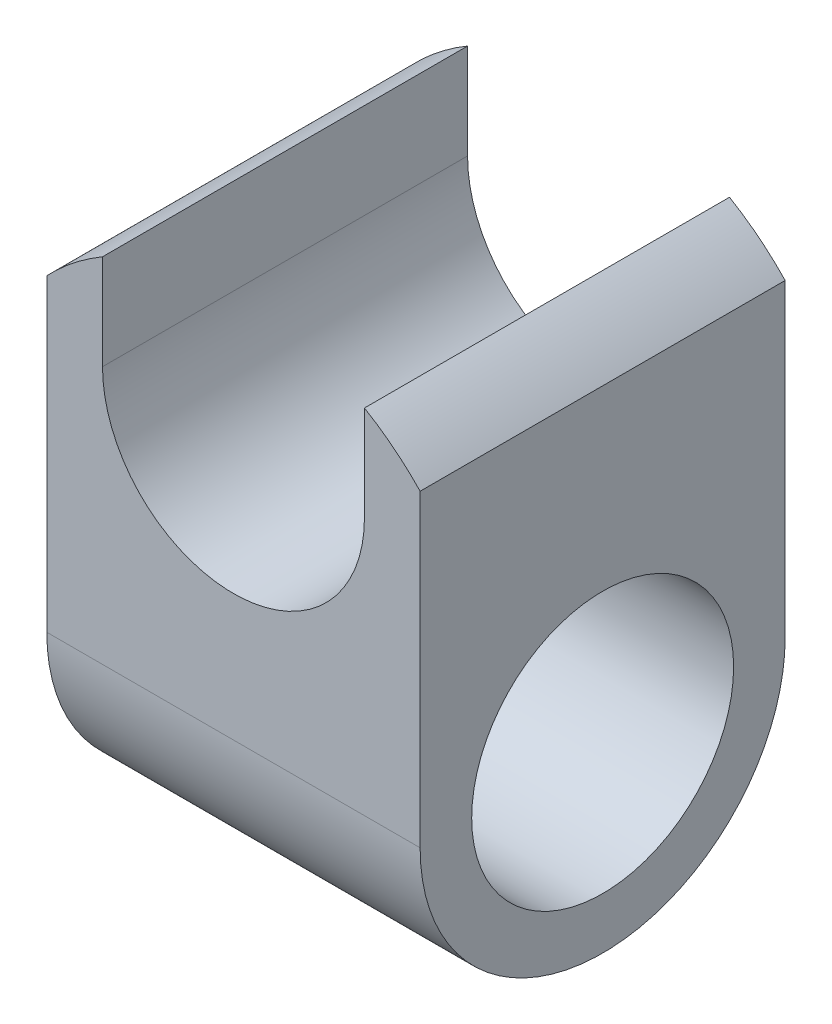
SolidWorks part; units mm, degrees
ref_plane "Front Plane" through (0, 0, 0) normal (0, 0, 1) x (1, 0, 0)
ref_plane "Top Plane" through (0, 0, 0) normal (0, 1, 0) x (1, 0, 0)
ref_plane "Right Plane" through (0, 0, 0) normal (1, 0, 0) x (0, 0, -1)
sketch "Sketch1" plane through (0, 0, 0) normal (0, 0, 1) x (1, 0, 0)
  line L3 (-6.35, 0) -> (-6.35, 5.9351)
  line L4 (6.35, 0) -> (6.35, 5.9351)
  line L5 (-9.05, 0) -> (-9.05, 5.4998)
  line L6 (9.05, 0) -> (9.05, 5.4998)
  arc A1 (-6.35, 0) -> (6.35, 0) centre (0, 0) ccw
  arc A2 (-9.05, 0) -> (9.05, 0) centre (0, 0) ccw
  circle A3 centre (0, 0) radius 9.05 construction
  circle A4 centre (0, 0) radius 6.35 construction
  ellipse E0 centre (0, -18.65) end of major axis (35, -18.65) minor radius 25 (-6.35, 5.9351) -> (-9.05, 5.4998) ccw
  ellipse E1 centre (0, -18.65) end of major axis (-35, -18.65) minor radius 25 (9.05, 5.4998) -> (6.35, 5.9351) ccw
  dimension "D1" = 12.7
  dimension "D2" = 2.7
  dimension "D3" = 25
  dimension "D4" = 35
extrude "Body spar link" add sketch "Sketch1" along normal mid plane 17.7
sketch "Sketch2" plane through (0, 0, 0) normal (1, 0, 0) x (0, 0, -1)
  line L1 (-8.85, -12.5) -> (-8.85, -2.5)
  line L6 (8.85, -2.5) -> (8.85, -12.5)
  line L8 (-8.85, -2.5) -> (8.85, -2.5)
  line L9 (-8.85, 0) -> (-8.85, -9.05) construction
  line L10 (8.85, -9.05) -> (8.85, 0) construction
  circle A0 centre (0, -12.5) radius 6.35
  arc A1 (-8.85, -12.5) -> (8.85, -12.5) centre (0, -12.5) ccw
  circle A2 centre (0, -12.5) radius 8.85 construction
  dimension "D1" = 12.7
  dimension "D3" = 2.5
  dimension "D4" = 10
  dimension "D2" = 2.5
extrude "Wing spar extrude" add sketch "Sketch2" along normal mid plane 18.1
sketch "Sketch3" plane through (0, -2.5, 0) normal (0, 1, 0) x (1, 0, 0)
  line L4 (9.05, 8.85) -> (8.6978, 8.85)
  line L5 (8.6978, 8.85) -> (8.6978, -8.85)
  line L6 (8.6978, -8.85) -> (9.05, -8.85)
  line L8 (9.05, 8.85) -> (8.6978, 8.85)
  line L10 (8.6978, -8.85) -> (9.05, -8.85)
  line L12 (-9.05, -8.85) -> (-8.6978, -8.85)
  line L13 (-8.6978, -8.85) -> (-8.6978, 8.85)
  line L14 (-8.6978, 8.85) -> (-9.05, 8.85)
  line L16 (-9.05, -8.85) -> (-8.6978, -8.85)
  line L18 (-8.6978, 8.85) -> (-9.05, 8.85)
  line L22 (-8.6978, -8.85) -> (-8.6978, 8.85)
  line L26 (8.6978, 8.85) -> (8.6978, -8.85)
  line L28 (-9.05, 8.85) -> (-9.05, -8.85)
  line L29 (-9.05, 8.85) -> (-9.05, -8.85)
  line L30 (9.05, -8.85) -> (9.05, 8.85)
  line L31 (9.05, -8.85) -> (9.05, 8.85)
  dimension "D1" = 0
  dimension "D2" = 0
extrude "Small cut completion" add sketch "Sketch3" along normal up to next
sketch "Sketch4" plane through (0, 0, -8.85) normal (0, 0, -1) x (-1, 0, 0)
  circle A0 centre (0, 0) radius 6.35
  arc A1 (5.8372, -2.5) -> (6.35, 0) centre (0, 0) ccw construction
extrude "Cut cleanup" cut sketch "Sketch4" against normal through all both and the other way through all
sketch "Sketch5" plane through (0, 0, -8.85) normal (0, 0, -1) x (-1, 0, 0)
  line L0 (-12.5, -6.15) -> (-22.5, -6.15)
  line L1 (12.5, -6.15) -> (22.5, -6.15)
  circle A0 centre (0, 0) radius 6.35 construction
  arc A1 (-6.35, 0) -> (6.35, 0) centre (0, 0) ccw construction
  arc A2 (12.5, -6.15) -> (-12.5, -6.15) centre (0, -6.15) ccw
  arc A3 (22.5, -6.15) -> (-22.5, -6.15) centre (0, -6.15) ccw
  circle A4 centre (0, -6.15) radius 12.5 construction
  circle A5 centre (0, -6.15) radius 22.5 construction
  dimension "D1" = 25
  dimension "D2" = 10
extrude "Edge rounding (to fit end cap of fuselage)" cut sketch "Sketch5" against normal through all both and the other way through all
sketch "Sketch6" plane through (9.05, 0, 0) normal (1, 0, 0) x (0, 0, -1)
  circle A0 centre (0, -12.5) radius 6.35 construction
  circle A1 centre (0, -12.5) radius 6.35
extrude "Wing spar cut cleanup" cut sketch "Sketch6" against normal through all both and the other way through all
